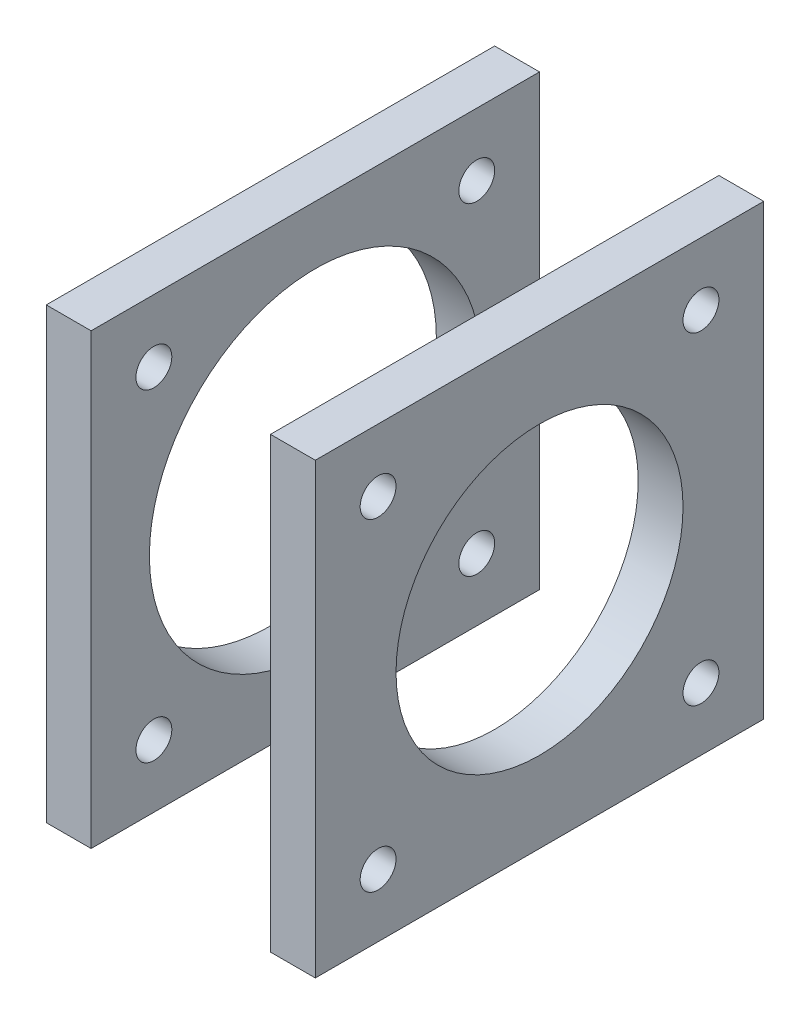
SolidWorks part; units mm, degrees
ref_plane "Front Plane" through (0, 0, 0) normal (0, 0, 1) x (1, 0, 0)
ref_plane "Top Plane" through (0, 0, 0) normal (0, 1, 0) x (1, 0, 0)
ref_plane "Right Plane" through (0, 0, 0) normal (1, 0, 0) x (0, 0, -1)
sketch "Sketch1" plane through (0, 0, 0) normal (1, 0, 0) x (0, 0, -1)
  line L0 (7.5692, 14.4151) -> (7.5692, -6.9155) construction
  line L1 (7.5692, -6.9155) -> (-17.8606, -6.9155) construction
  line L2 (-10.4308, 11.0845) -> (25.5692, -24.9155) construction
  line L4 (-17.4308, -31.9155) -> (32.5692, -31.9155)
  line L5 (-17.4308, -31.9155) -> (-17.4308, 18.0845)
  line L6 (-17.4308, 18.0845) -> (32.5692, 18.0845)
  line L7 (32.5692, -31.9155) -> (32.5692, 18.0845)
  line L8 (-17.4308, -31.9155) -> (32.5692, 18.0845) construction
  line L9 (-17.4308, 18.0845) -> (32.5692, -31.9155) construction
  circle A0 centre (-10.4308, 11.0845) radius 2
  circle A1 centre (-10.4308, -24.9155) radius 2
  circle A2 centre (25.5692, -24.9155) radius 2
  circle A3 centre (25.5692, 11.0845) radius 2
  circle A4 centre (7.5692, -6.9155) radius 18.5
  dimension "D1" = 4
  dimension "D4" = 37
  dimension "D2" = 18
  dimension "D3" = 18
  dimension "D5" = 50
  dimension "D6" = 50
extrude "Boss-Extrude1" add sketch "Sketch1" along normal blind 5
ref_plane "Plane1" through (25, 0, 0) normal (1, 0, 0) x (0, 0, -1)
sketch "Sketch4" plane through (25, 0, 0) normal (1, 0, 0) x (0, 0, -1)
  line L0 (-17.4308, -31.9155) -> (32.5692, -31.9155) construction
  line L1 (32.5692, 18.0845) -> (-17.4308, 18.0845) construction
  line L2 (32.5692, -31.9155) -> (32.5692, 18.0845) construction
  line L3 (-17.4308, 18.0845) -> (-17.4308, -31.9155) construction
  line L4 (-17.4308, -31.9155) -> (32.5692, -31.9155)
  line L5 (32.5692, 18.0845) -> (-17.4308, 18.0845)
  line L6 (32.5692, -31.9155) -> (32.5692, 18.0845)
  line L7 (-17.4308, 18.0845) -> (-17.4308, -31.9155)
  circle A1 centre (-10.4308, -24.9155) radius 2 construction
  circle A2 centre (-10.4308, 11.0845) radius 2 construction
  circle A3 centre (25.5692, 11.0845) radius 2 construction
  circle A4 centre (25.5692, -24.9155) radius 2 construction
  circle A6 centre (-10.4308, -24.9155) radius 2
  circle A7 centre (-10.4308, 11.0845) radius 2
  circle A8 centre (25.5692, 11.0845) radius 2
  circle A9 centre (25.5692, -24.9155) radius 2
  circle A10 centre (7.5692, -6.9155) radius 16
  dimension "D1" = 32
extrude "Boss-Extrude2" add sketch "Sketch4" along normal blind 5 separate body
